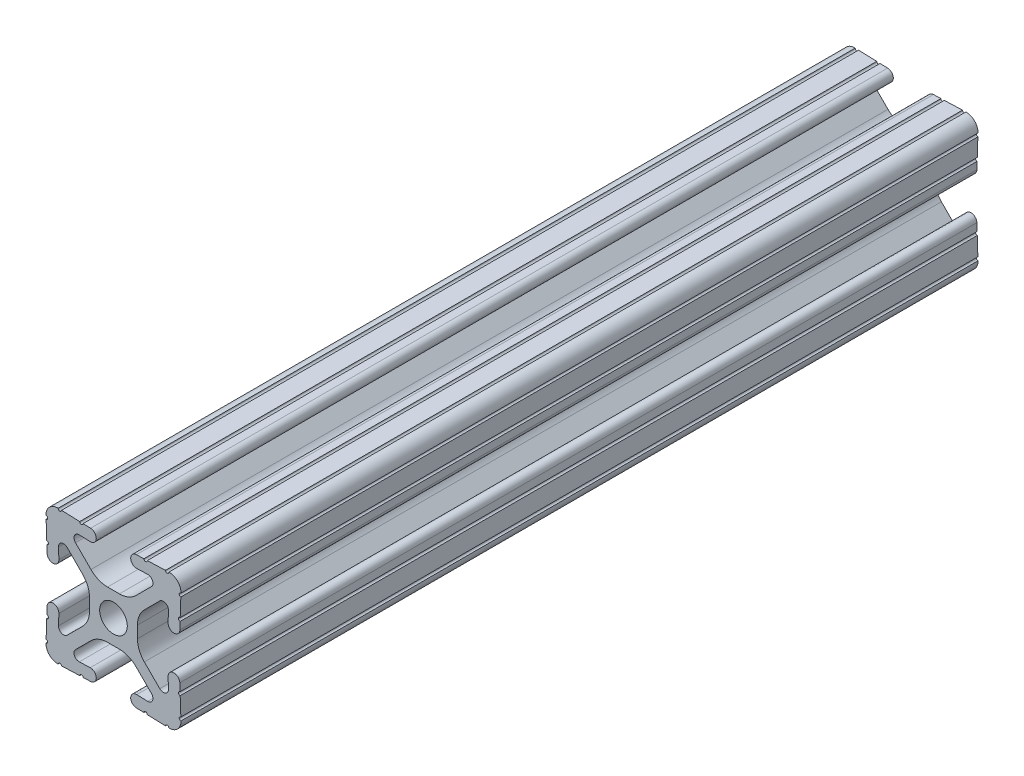
SolidWorks part; units mm, degrees
ref_plane "Front Plane" through (0, 0, 0) normal (0, 0, 1) x (1, 0, 0)
ref_plane "Top Plane" through (0, 0, 0) normal (0, 1, 0) x (1, 0, 0)
ref_plane "Right Plane" through (0, 0, 0) normal (1, 0, 0) x (0, 0, -1)
sketch "Sketch1" plane through (0, 0, 0) normal (0, 0, 1) x (1, 0, 0)
  line L0 (0, 12.7) -> (-12.7814, 12.7) construction
  line L1 (-4.5085, 0) -> (-4.5085, 2.9459)
  line L2 (-6.0437, 12.5461) -> (-10.0976, 12.6876) construction
  line L3 (-11.5616, 12.4229) -> (-4.3159, 12.1699) construction
  line L4 (-6.4364, 10.3486) -> (-6.3592, 12.5571) construction
  line L6 (-2.9459, 4.5085) -> (0, 4.5085)
  line L7 (0, 0) -> (0, 12.7) construction
  line L8 (0, 0) -> (-12.7814, 0) construction
  line L9 (0.7813, 0.7813) -> (-0.7813, -0.7813) construction
  line L10 (-2.9459, 4.5085) -> (-7.1484, 8.711)
  line L11 (-4.5085, 2.9459) -> (-8.711, 7.1484)
  line L13 (0, 0) -> (-12.7814, 12.7814) construction
  line L14 (-10.4131, 12.6987) -> (-4.3048, 12.4853)
  line L15 (-4.3048, 12.4853) -> (-4.382, 10.2769) construction
  line L16 (-4.382, 10.2769) -> (-6.4364, 10.3486)
  line L17 (-12.6987, 10.4131) -> (-12.4853, 4.3048)
  line L18 (-10.2769, 4.382) -> (-10.3486, 6.4364)
  circle A0 centre (0, 0) radius 2.6035
  arc A1 (-4.382, 10.2769) -> (-4.3048, 12.4853) centre (-4.3434, 11.3811) ccw
  arc A2 (-7.1484, 8.711) -> (-6.4364, 10.3486) centre (-6.4698, 9.3896) cw
  arc A3 (-8.711, 7.1484) -> (-10.3486, 6.4364) centre (-9.3896, 6.4698) ccw
  arc A4 (-10.2769, 4.382) -> (-12.4853, 4.3048) centre (-11.3811, 4.3434) cw
  arc A5 (-10.4131, 12.6987) -> (-12.6987, 10.4131) centre (-10.4902, 10.4902) ccw
  arc A6 (-10.4131, 12.6987) -> (-9.7821, 12.6766) centre (-10.0976, 12.6876) ccw
  arc A7 (-6.3592, 12.5571) -> (-5.7282, 12.5351) centre (-6.0437, 12.5461) ccw
  arc A8 (-12.5571, 6.3592) -> (-12.5351, 5.7282) centre (-12.5461, 6.0437) cw
  arc A9 (-12.6987, 10.4131) -> (-12.6766, 9.7821) centre (-12.6876, 10.0976) cw
  dimension "D1" = 5.207
  dimension "D5" = 14.859
  dimension "D9" = 2
  dimension "D2" = 25.4
  dimension "D12" = 0.6314
  dimension "D10" = 2.2098
  dimension "D3" = 9.017
  dimension "D4" = 9.017
  dimension "D6" = 25.4
  dimension "D7" = 6.477
  dimension "D8" = 2.2098
  dimension "D11" = 12.7
sketch "Sketch3" plane through (0, 0, 0) normal (0, 0, 1) x (1, 0, 0)
  line L0 (-2.9459, 4.5085) -> (0, 4.5085) construction
  line L1 (-2.9459, 4.5085) -> (-7.1484, 8.711) construction
  line L2 (-4.382, 10.2769) -> (-6.4364, 10.3486) construction
  line L3 (-10.4131, 12.6987) -> (-4.3048, 12.4853) construction
  line L4 (-4.5085, 0) -> (-4.5085, 2.9459) construction
  line L5 (-4.5085, 2.9459) -> (-8.711, 7.1484) construction
  line L6 (-10.2769, 4.382) -> (-10.3486, 6.4364) construction
  line L7 (-12.6987, 10.4131) -> (-12.4853, 4.3048) construction
  line L8 (-1.1153, 4.5085) -> (1.1153, 4.5085)
  line L9 (-4.2404, 5.803) -> (-7.1484, 8.711)
  line L10 (-4.382, 10.2769) -> (-6.4364, 10.3486)
  line L11 (-9.7821, 12.6766) -> (-6.3592, 12.5571)
  line L12 (-4.5085, -1.1153) -> (-4.5085, 1.1153)
  line L13 (-5.803, 4.2404) -> (-8.711, 7.1484)
  line L14 (-10.2769, 4.382) -> (-10.3486, 6.4364)
  line L15 (-12.6766, 9.7821) -> (-12.5571, 6.3592)
  line L16 (-5.7282, 12.5351) -> (-4.3048, 12.4853)
  line L17 (-12.5351, 5.7282) -> (-12.4853, 4.3048)
  line L18 (0, 0) -> (0, 12.7) construction
  line L19 (0, 0) -> (-12.7814, 0) construction
  line L20 (12.5351, 5.7282) -> (12.4853, 4.3048)
  line L21 (5.7282, 12.5351) -> (4.3048, 12.4853)
  line L22 (12.6766, 9.7821) -> (12.5571, 6.3592)
  line L23 (10.2769, 4.382) -> (10.3486, 6.4364)
  line L24 (5.803, 4.2404) -> (8.711, 7.1484)
  line L25 (4.5085, -1.1153) -> (4.5085, 1.1153)
  line L26 (9.7821, 12.6766) -> (6.3592, 12.5571)
  line L27 (4.382, 10.2769) -> (6.4364, 10.3486)
  line L28 (4.2404, 5.803) -> (7.1484, 8.711)
  line L29 (4.2404, -5.803) -> (7.1484, -8.711)
  line L30 (4.382, -10.2769) -> (6.4364, -10.3486)
  line L31 (9.7821, -12.6766) -> (6.3592, -12.5571)
  line L32 (5.803, -4.2404) -> (8.711, -7.1484)
  line L33 (10.2769, -4.382) -> (10.3486, -6.4364)
  line L34 (12.6766, -9.7821) -> (12.5571, -6.3592)
  line L35 (5.7282, -12.5351) -> (4.3048, -12.4853)
  line L36 (12.5351, -5.7282) -> (12.4853, -4.3048)
  line L37 (-12.5351, -5.7282) -> (-12.4853, -4.3048)
  line L38 (-5.7282, -12.5351) -> (-4.3048, -12.4853)
  line L39 (-12.6766, -9.7821) -> (-12.5571, -6.3592)
  line L40 (-10.2769, -4.382) -> (-10.3486, -6.4364)
  line L41 (-5.803, -4.2404) -> (-8.711, -7.1484)
  line L42 (-9.7821, -12.6766) -> (-6.3592, -12.5571)
  line L43 (-4.382, -10.2769) -> (-6.4364, -10.3486)
  line L44 (-4.2404, -5.803) -> (-7.1484, -8.711)
  line L45 (-1.1153, -4.5085) -> (1.1153, -4.5085)
  arc A0 (-10.4131, 12.6987) -> (-9.7821, 12.6766) centre (-10.0976, 12.6876) ccw construction
  arc A1 (-6.4364, 10.3486) -> (-7.1484, 8.711) centre (-6.4698, 9.3896) ccw construction
  arc A2 (-4.382, 10.2769) -> (-4.3048, 12.4853) centre (-4.3434, 11.3811) ccw construction
  arc A3 (-8.711, 7.1484) -> (-10.3486, 6.4364) centre (-9.3896, 6.4698) ccw construction
  arc A4 (-12.4853, 4.3048) -> (-10.2769, 4.382) centre (-11.3811, 4.3434) ccw construction
  arc A5 (-6.3592, 12.5571) -> (-5.7282, 12.5351) centre (-6.0437, 12.5461) ccw construction
  arc A6 (-10.4131, 12.6987) -> (-12.6987, 10.4131) centre (-10.4902, 10.4902) ccw construction
  arc A7 (-12.6766, 9.7821) -> (-12.6987, 10.4131) centre (-12.6876, 10.0976) ccw construction
  arc A8 (-12.5351, 5.7282) -> (-12.5571, 6.3592) centre (-12.5461, 6.0437) ccw construction
  arc A9 (-10.4131, 12.6987) -> (-9.7821, 12.6766) centre (-10.0976, 12.6876) ccw
  arc A10 (-6.4364, 10.3486) -> (-7.1484, 8.711) centre (-6.4698, 9.3896) ccw
  arc A11 (-4.382, 10.2769) -> (-4.3048, 12.4853) centre (-4.3434, 11.3811) ccw
  arc A12 (-8.711, 7.1484) -> (-10.3486, 6.4364) centre (-9.3896, 6.4698) ccw
  arc A13 (-12.4853, 4.3048) -> (-10.2769, 4.382) centre (-11.3811, 4.3434) ccw
  arc A14 (-6.3592, 12.5571) -> (-5.7282, 12.5351) centre (-6.0437, 12.5461) ccw
  arc A15 (-10.4131, 12.6987) -> (-12.6987, 10.4131) centre (-10.4902, 10.4902) ccw
  arc A16 (-12.6766, 9.7821) -> (-12.6987, 10.4131) centre (-12.6876, 10.0976) ccw
  arc A17 (-12.5351, 5.7282) -> (-12.5571, 6.3592) centre (-12.5461, 6.0437) ccw
  arc A18 (-1.1153, 4.5085) -> (-4.2404, 5.803) centre (-1.1153, 8.9281) cw
  arc A19 (4.5085, 1.1153) -> (5.803, 4.2404) centre (8.9281, 1.1153) cw
  arc A20 (1.1153, 4.5085) -> (4.2404, 5.803) centre (1.1153, 8.9281) ccw
  arc A21 (-4.5085, 1.1153) -> (-5.803, 4.2404) centre (-8.9281, 1.1153) ccw
  arc A22 (12.5351, 5.7282) -> (12.5571, 6.3592) centre (12.5461, 6.0437) cw
  arc A23 (12.6766, 9.7821) -> (12.6987, 10.4131) centre (12.6876, 10.0976) cw
  arc A24 (10.4131, 12.6987) -> (12.6987, 10.4131) centre (10.4902, 10.4902) cw
  arc A25 (6.3592, 12.5571) -> (5.7282, 12.5351) centre (6.0437, 12.5461) cw
  arc A26 (12.4853, 4.3048) -> (10.2769, 4.382) centre (11.3811, 4.3434) cw
  arc A27 (8.711, 7.1484) -> (10.3486, 6.4364) centre (9.3896, 6.4698) cw
  arc A28 (4.382, 10.2769) -> (4.3048, 12.4853) centre (4.3434, 11.3811) cw
  arc A29 (6.4364, 10.3486) -> (7.1484, 8.711) centre (6.4698, 9.3896) cw
  arc A30 (10.4131, 12.6987) -> (9.7821, 12.6766) centre (10.0976, 12.6876) cw
  arc A31 (10.4131, -12.6987) -> (9.7821, -12.6766) centre (10.0976, -12.6876) ccw
  arc A32 (6.4364, -10.3486) -> (7.1484, -8.711) centre (6.4698, -9.3896) ccw
  arc A33 (4.382, -10.2769) -> (4.3048, -12.4853) centre (4.3434, -11.3811) ccw
  arc A34 (8.711, -7.1484) -> (10.3486, -6.4364) centre (9.3896, -6.4698) ccw
  arc A35 (12.4853, -4.3048) -> (10.2769, -4.382) centre (11.3811, -4.3434) ccw
  arc A36 (6.3592, -12.5571) -> (5.7282, -12.5351) centre (6.0437, -12.5461) ccw
  arc A37 (10.4131, -12.6987) -> (12.6987, -10.4131) centre (10.4902, -10.4902) ccw
  arc A38 (12.6766, -9.7821) -> (12.6987, -10.4131) centre (12.6876, -10.0976) ccw
  arc A39 (12.5351, -5.7282) -> (12.5571, -6.3592) centre (12.5461, -6.0437) ccw
  arc A40 (-4.5085, -1.1153) -> (-5.803, -4.2404) centre (-8.9281, -1.1153) cw
  arc A41 (1.1153, -4.5085) -> (4.2404, -5.803) centre (1.1153, -8.9281) cw
  arc A42 (4.5085, -1.1153) -> (5.803, -4.2404) centre (8.9281, -1.1153) ccw
  arc A43 (-1.1153, -4.5085) -> (-4.2404, -5.803) centre (-1.1153, -8.9281) ccw
  arc A44 (-12.5351, -5.7282) -> (-12.5571, -6.3592) centre (-12.5461, -6.0437) cw
  arc A45 (-12.6766, -9.7821) -> (-12.6987, -10.4131) centre (-12.6876, -10.0976) cw
  arc A46 (-10.4131, -12.6987) -> (-12.6987, -10.4131) centre (-10.4902, -10.4902) cw
  arc A47 (-6.3592, -12.5571) -> (-5.7282, -12.5351) centre (-6.0437, -12.5461) cw
  arc A48 (-12.4853, -4.3048) -> (-10.2769, -4.382) centre (-11.3811, -4.3434) cw
  arc A49 (-8.711, -7.1484) -> (-10.3486, -6.4364) centre (-9.3896, -6.4698) cw
  arc A50 (-4.382, -10.2769) -> (-4.3048, -12.4853) centre (-4.3434, -11.3811) cw
  arc A51 (-6.4364, -10.3486) -> (-7.1484, -8.711) centre (-6.4698, -9.3896) cw
  arc A52 (-10.4131, -12.6987) -> (-9.7821, -12.6766) centre (-10.0976, -12.6876) cw
  circle A53 centre (0, 0) radius 2.6035 construction
  circle A54 centre (0, 0) radius 2.6035
  point P135 (4.5085, 0)
  dimension "D2" = 4.4196
extrude "Extrude1" add sketch "Sketch3" along normal mid plane 150
equation "\"D10@Sketch1\" = \"D8@Sketch1\""
equation "\"D11@Sketch1\" = \"D6@Sketch1\"/2"
equation "\"D12@Sketch1\" = \"D8@Sketch1\"/3.5"
equation "\"D2@Sketch3\" = \"D8@Sketch1\"*2"
